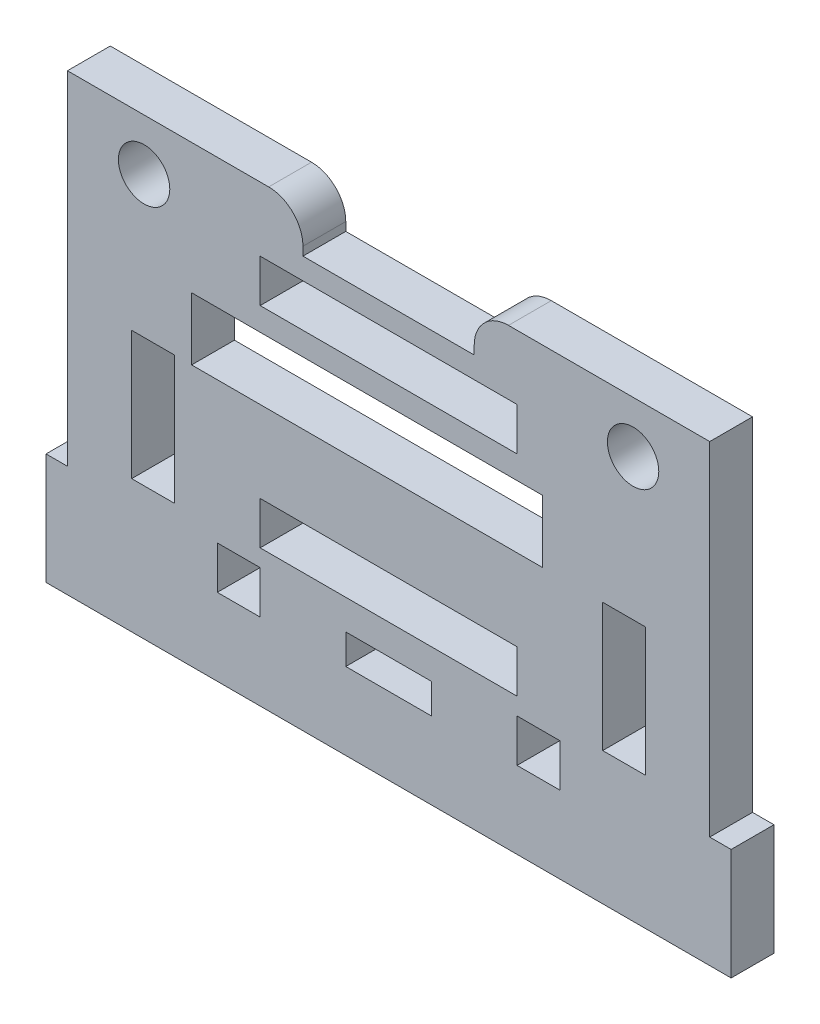
SolidWorks part; units mm, degrees
ref_plane "前视基准面" through (0, 0, 0) normal (0, 0, 1) x (1, 0, 0)
ref_plane "上视基准面" through (0, 0, 0) normal (0, 1, 0) x (1, 0, 0)
ref_plane "右视基准面" through (0, 0, 0) normal (1, 0, 0) x (0, 0, -1)
sketch "草图1" plane through (0, 0, 0) normal (0, 0, 1) x (1, 0, 0)
  line L0 (0, 0) -> (-80, 0)
  line L1 (-80, 0) -> (-80, 13)
  line L2 (-80, 13) -> (-77.5, 13)
  line L3 (-77.5, 13) -> (-77.5, 53)
  line L4 (-77.5, 53) -> (-54, 53)
  line L5 (-2.5, 53) -> (-2.5, 13)
  line L6 (-2.5, 13) -> (0, 13)
  line L7 (0, 13) -> (0, 0)
  line L8 (-86.7959, 43) -> (14.3654, 43) construction
  line L9 (-68.55, 74.9247) -> (-68.55, -9.3763) construction
  line L10 (-11.45, -7.828) -> (-11.45, 70.2796) construction
  line L11 (-70, 69.4784) -> (-70, -3.8242) construction
  line L12 (-55, 45.5) -> (-25, 45.5)
  line L13 (-55, 45.5) -> (-55, 40.5)
  line L14 (-55, 40.5) -> (-25, 40.5)
  line L15 (-25, 45.5) -> (-25, 40.5)
  line L16 (-55, 45.5) -> (-25, 40.5) construction
  line L17 (-55, 40.5) -> (-25, 45.5) construction
  line L18 (-10, -2.6643) -> (-10, 71.2181) construction
  line L19 (-40, 69.4784) -> (-40, -3.8242) construction
  line L20 (-109.5141, 47) -> (59.3771, 47) construction
  line L21 (-70, 30.5) -> (-65, 30.5)
  line L22 (-70, 30.5) -> (-70, 15.5)
  line L23 (-70, 15.5) -> (-65, 15.5)
  line L24 (-65, 30.5) -> (-65, 15.5)
  line L25 (-10, 30.5) -> (-15, 30.5)
  line L26 (-10, 30.5) -> (-10, 15.5)
  line L27 (-10, 15.5) -> (-15, 15.5)
  line L28 (-15, 30.5) -> (-15, 15.5)
  line L29 (-26, 53) -> (-2.5, 53)
  line L30 (-55, 16) -> (-50, 16)
  line L31 (-50, 49) -> (-50, 48)
  line L32 (-50, 48) -> (-30, 48)
  line L33 (-30, 49) -> (-30, 48)
  line L34 (-55, 21) -> (-25, 21)
  line L35 (-55, 21) -> (-55, 16)
  line L36 (-50, 16) -> (-30, 16)
  line L37 (-25, 21) -> (-25, 16)
  line L38 (-30, 16) -> (-25, 16)
  line L39 (-61.6343, 14) -> (-21.8599, 14) construction
  line L41 (-55, 14) -> (-60, 14)
  line L42 (-55, 14) -> (-55, 9)
  line L43 (-55, 9) -> (-60, 9)
  line L44 (-60, 14) -> (-60, 9)
  line L45 (-25, 14) -> (-20, 14)
  line L46 (-45, 12.5) -> (-35, 12.5)
  line L47 (-45, 12.5) -> (-45, 9)
  line L48 (-45, 9) -> (-35, 9)
  line L49 (-35, 12.5) -> (-35, 9)
  line L50 (-25, 14) -> (-25, 9)
  line L51 (-25, 9) -> (-20, 9)
  line L52 (-20, 14) -> (-20, 9)
  line L53 (-63, 30.5) -> (-22, 30.5)
  line L54 (-63, 30.5) -> (-63, 37.8)
  line L55 (-63, 37.8) -> (-22, 37.8)
  line L56 (-22, 30.5) -> (-22, 37.8)
  circle A0 centre (-68.55, 47) radius 3
  circle A1 centre (-11.45, 47) radius 3
  arc A2 (-26, 53) -> (-30, 49) centre (-26, 49) ccw
  arc A3 (-54, 53) -> (-50, 49) centre (-54, 49) cw
  point P19 (-40, 43)
  point P48 (-50, 53)
  dimension "D10" = 30
  dimension "D26" = 4
  dimension "D27" = 30
  dimension "D1" = 80
  dimension "D2" = 75
  dimension "D3" = 2.5
  dimension "D4" = 13
  dimension "D5" = 40
  dimension "D6" = 13
  dimension "D7" = 57.1
  dimension "D8" = 8.95
  dimension "D9" = 43
  dimension "D11" = 5
  dimension "D12" = 0
  dimension "D13" = 37.5
  dimension "D14" = 60
  dimension "D15" = 30
  dimension "D16" = 15
  dimension "D17" = 15
  dimension "D18" = 5
  dimension "D19" = 5
  dimension "D20" = 10
  dimension "D21" = 10
  dimension "D22" = 4
  dimension "D23" = 10
  dimension "D24" = 10
  dimension "D25" = 5
  dimension "D28" = 5
  dimension "D29" = 16
  dimension "D30" = 10
  dimension "D31" = 3.5
  dimension "D32" = 5
  dimension "D33" = 2
  dimension "D34" = 41
  dimension "D35" = 7.3
  dimension "D36" = 0
  dimension "D37" = 2
extrude "凸台-拉伸1" add sketch "草图1" along normal blind 5
